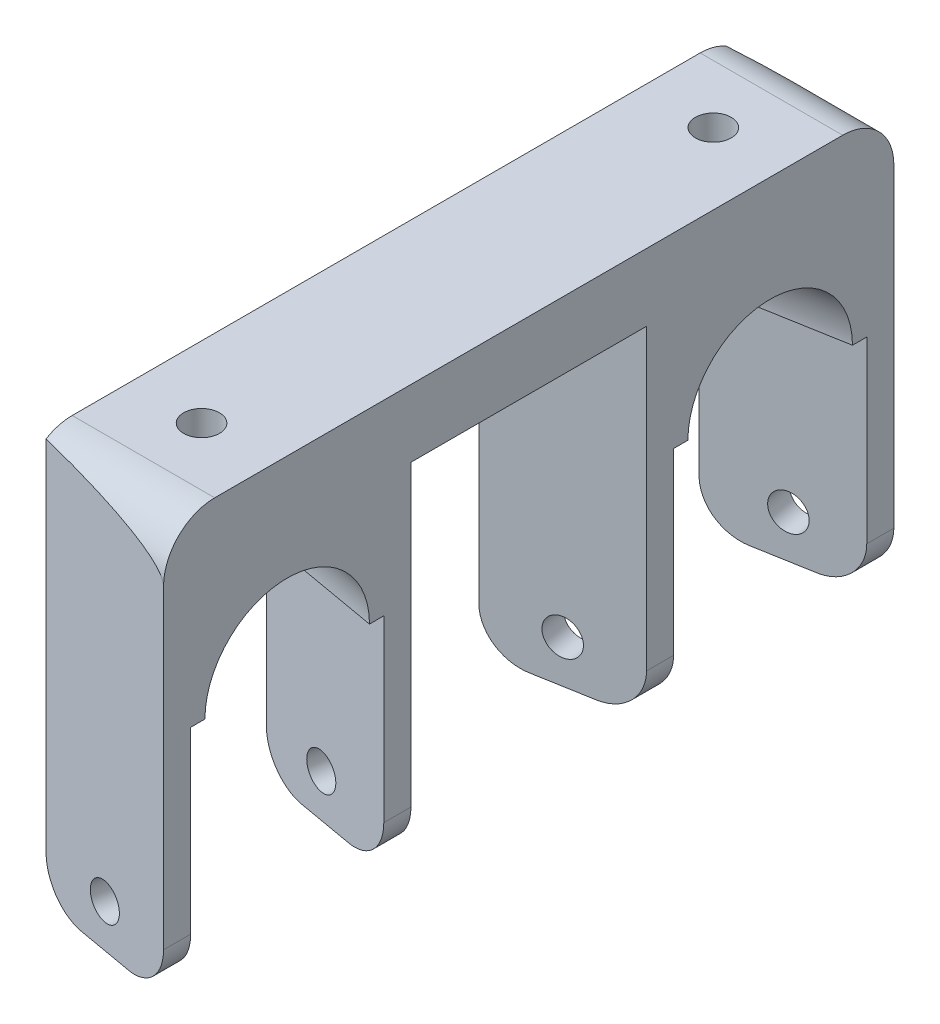
SolidWorks part; units mm, degrees
ref_plane "前视基准面" through (0, 0, 0) normal (0, 0, 1) x (1, 0, 0)
ref_plane "上视基准面" through (0, 0, 0) normal (0, 1, 0) x (1, 0, 0)
ref_plane "右视基准面" through (0, 0, 0) normal (1, 0, 0) x (0, 0, -1)
sketch "Sketch1" plane through (0, 0, 0) normal (0, 0, 1) x (1, 0, 0)
  line L0 (-49.7904, -17.4126) -> (50.2096, -17.4126)
  line L1 (50.2096, -17.4126) -> (50.2096, -9.5139)
  line L2 (50.2096, -9.5139) -> (43.3729, -9.5139) construction
  line L3 (22.3729, 11.7021) -> (43.3729, 11.7021) construction
  line L4 (-49.7904, -1.2703) -> (-49.7904, -17.4126)
  circle A0 centre (22.3729, 11.7021) radius 21
  arc A1 (50.2096, -9.5139) -> (-10.864, 22.6705) centre (22.3729, 11.7021) ccw
  spline S0 degree 2 poles (-49.7904, -1.2703) (-17.5579, 2.3865) (-10.864, 22.6705) knots 0 0 0 1 1 1
  dimension "D3" = 42
  dimension "D1" = 100
extrude "Boss-Extrude1" add sketch "Sketch1" along normal blind 70
sketch "Sketch2" plane through (0, -17.4126, 0) normal (0, -1, 0) x (1, 0, 0)
  line L0 (3.5012, 70) -> (3.5012, 0)
  line L4 (-49.7904, 70) -> (50.2096, 70) construction
  line L5 (3.5012, 60) -> (63.5012, 60)
  line L8 (3.5012, 10) -> (3.5012, 60)
  line L10 (63.5012, 60) -> (63.5012, 10)
  line L11 (63.5012, 10) -> (3.5012, 10)
  line L12 (-49.7904, 0) -> (50.2096, 0) construction
extrude "Cut-Extrude6" cut sketch "Sketch2" against normal blind 1000
sketch "Sketch4" plane through (0, 0, 60) normal (0, 0, -1) x (-1, 0, 0)
  line L0 (-3.5012, -17.4126) -> (-33.5012, -17.4126)
  line L1 (-3.5012, -17.4126) -> (-50.2096, -17.4126) construction
  line L2 (-33.5012, -17.4126) -> (-33.5012, -6.107)
  line L3 (-33.5012, -6.107) -> (-3.5012, 2.4902)
  line L4 (-3.5012, 2.4902) -> (-3.5012, -17.4126)
  arc A0 (-3.5012, 20.9139) -> (-3.5012, 2.4902) centre (-22.3729, 11.7021) ccw construction
  dimension "D1" = 30
extrude "Cut-Extrude7" cut sketch "Sketch4" against normal mid plane 1000
ref_plane "Plane1" through (50.2096, -9.5139, 0) normal (0, 1, 0) x (1, 0, 0)
sketch "Sketch6" plane through (0, -17.4126, 0) normal (0, -1, 0) x (1, 0, 0)
  line L0 (3.5012, 10) -> (-24.7923, 11.9649)
  line L1 (-41.5452, 29.9216) -> (-41.5452, 40.0784)
  line L2 (3.5012, 10) -> (3.5012, 60)
  line L3 (2.8084, 0.024) -> (-25.4851, 1.9889)
  line L4 (-51.5452, 29.9216) -> (-51.5452, 40.0784)
  line L5 (-41.9015, 35) -> (-41.5452, 35) construction
  line L6 (3.5012, 60) -> (-24.7923, 58.0351)
  line L7 (2.8084, 69.976) -> (-25.4851, 68.0111)
  line L8 (2.8084, 0.024) -> (-51.5452, 0.024)
  line L9 (-51.5452, 0.024) -> (-51.5452, 69.976)
  line L10 (-51.5452, 69.976) -> (2.8084, 69.976)
  arc A0 (-24.7923, 11.9649) -> (-41.5452, 29.9216) centre (-23.5452, 29.9216) cw
  arc A1 (-24.7923, 58.0351) -> (-41.5452, 40.0784) centre (-23.5452, 40.0784) ccw
  arc A2 (-25.4851, 1.9889) -> (-51.5452, 29.9216) centre (-23.5452, 29.9216) cw
  arc A3 (-25.4851, 68.0111) -> (-51.5452, 40.0784) centre (-23.5452, 40.0784) ccw
  line M8 (3.5012, 0) -> (3.5012, 70)
  dimension "D1" = 18
  dimension "D3" = 10
extrude "Cut-Extrude9" cut sketch "Sketch6" against normal blind 10 contours L6 A1 L1 A0 L0 M8
sketch "Sketch7" plane through (0, -17.4126, 0) normal (0, -1, 0) x (1, 0, 0)
  line L0 (-23.1446, 0) -> (-26.7904, 0)
  line L1 (-49.7904, 0) -> (3.5012, 0) construction
  line L2 (-49.7904, 70) -> (-49.7904, 0) construction
  line L3 (-26.7904, 0) -> (-51.7904, 0)
  line L4 (-26.7904, 70) -> (-23.1446, 70)
  line L5 (-49.7904, 70) -> (3.5012, 70) construction
  line L6 (-51.7904, 25) -> (-51.7904, 45)
  line L7 (-51.7904, 0) -> (-51.7904, 70)
  line L8 (-51.7904, 70) -> (-26.7904, 70)
  arc A0 (-51.7904, 45) -> (-26.7904, 70) centre (-26.7904, 45) cw
  arc A1 (-26.7904, 0) -> (-51.7904, 25) centre (-26.7904, 25) cw
  point P17 (-51.7904, 0)
  line M5 (3.5012, 70) -> (-49.7904, 70)
  line M6 (-49.7904, 70) -> (-49.7904, 0)
  line M7 (-49.7904, 0) -> (3.5012, 0)
  dimension "D2" = 25
  dimension "D1" = 2
extrude "Cut-Extrude10" cut sketch "Sketch7" against normal blind 30 contours A1 M7 M6 | A1 L7 L3 M6 | L7 A0 L8 M6 | A0 M6 M5 | A1 A0 L6 M6
sketch "Sketch8" plane through (0, 0, 0) normal (0, 1, 0) x (1, 0, 0)
  line L0 (3.5012, -10) -> (3.5012, -60)
  point P4 (3.5012, -35)
ref_plane "Plane3" through (0, 0, 35) normal (0, 0, -1) x (-1, 0, 0)
fillet "Fillet1" radius 10 1 edges at (-49.7904, -1.2703, 35)
sketch "Sketch13" plane through (0, 0, 35) normal (0, 0, -1) x (-1, 0, 0)
  line L0 (-3.5012, 2.4902) -> (-3.5012, 64.347) construction
  line L1 (-3.5012, 41.1785) -> (-24.8842, 72.5913)
  line L2 (-24.8842, 72.5913) -> (-12.5264, 81.0034)
  line L3 (-12.5264, 81.0034) -> (8.0383, 50.7928)
  line L4 (11.0572, 45.7425) -> (33.7918, 2.0647)
  arc A0 (-3.5012, 41.1785) -> (10.864, 22.6705) centre (-22.3729, 11.7021) cw
  arc A1 (10.864, 22.6705) -> (-50.2096, -9.5139) centre (-22.3729, 11.7021) ccw construction
  arc A2 (8.0383, 50.7928) -> (11.0572, 45.7425) centre (-33.2944, 22.6572) cw
  parabola Q0 (26.7904, 4.95) -> (41.7718, -0.0245) focus (25.8084, 23.5741) apex (14.0807, 15.9386) construction
  spline S0 degree 2 poles (10.864, 22.6705) (15.6943, 8.0336) (33.7918, 2.0647) knots 0 0 0 1 1 1
  dimension "D3" = 50
  dimension "D1" = 38
  dimension "D2" = 14.9492
extrude "Boss-Extrude4" add sketch "Sketch13" along normal mid plane 50
fillet "Fillet3" radius 10 2 edges at (18.7053, 76.7973, 10) (18.7053, 76.7973, 60)
sketch "Sketch14" plane through (-29.1201, 19.8224, 0) normal (-0.8267, 0.5627, 0) x (0, 0, 1)
  line L0 (10, 55.7643) -> (60, 55.7643) construction
  line L1 (10, 37.4648) -> (10, 64.0105) construction
  line L2 (60, 37.4648) -> (60, 64.0105) construction
  circle A0 centre (35, 55.7643) radius 4
extrude "Cut-Extrude11" cut sketch "Sketch14" against normal through all
sketch "Sketch16" plane through (0, 0, 70) normal (0, 0, 1) x (1, 0, 0)
  line L0 (3.5012, 2.4902) -> (3.5012, -17.4126) construction
  line L1 (33.5012, -17.4126) -> (33.5012, -6.107) construction
  line L2 (3.5012, -0.5498) -> (3.5012, 2.4902)
  line L3 (33.5012, -7.8533) -> (33.5012, -6.107)
  arc A0 (3.5012, -0.5498) -> (33.5012, -7.8533) centre (22.3729, 11.7021) cw
  arc A1 (3.5012, 2.4902) -> (33.5012, -6.107) centre (22.3729, 11.7021) cw
  line M4 (3.5012, -17.4126) -> (3.5012, 2.4902)
  arc M5 (3.5012, 2.4902) -> (33.5012, -6.107) centre (22.3729, 11.7021) cw
  line M6 (33.5012, -6.107) -> (33.5012, -17.4126)
extrude "Cut-Extrude12" cut sketch "Sketch16" against normal blind 2 contours A0 M4 M5 M6
sketch "Sketch17" plane through (0, 0, 0) normal (0, 0, -1) x (-1, 0, 0)
  line L0 (-3.5012, 2.4902) -> (-3.5012, -17.4126) construction
  line L1 (-33.5012, -17.4126) -> (-33.5012, -6.107) construction
  line L2 (-33.5012, -7.8533) -> (-33.5012, -6.107)
  line L3 (-3.5012, -0.5498) -> (-3.5012, 2.4902)
  arc A0 (-3.5012, -0.5498) -> (-33.5012, -7.8533) centre (-22.3729, 11.7021) ccw
  arc A1 (-3.5012, 2.4902) -> (-33.5012, -6.107) centre (-22.3729, 11.7021) ccw
  arc A2 (-3.5012, 2.4902) -> (-33.5012, -6.107) centre (-22.3729, 11.7021) ccw construction
  line M7 (-33.5012, -17.4126) -> (-33.5012, -6.107)
  arc M8 (-33.5012, -6.107) -> (-3.5012, 2.4902) centre (-22.3729, 11.7021) cw
  line M9 (-3.5012, 2.4902) -> (-3.5012, -17.4126)
extrude "Cut-Extrude13" cut sketch "Sketch17" against normal blind 2 contours A0 M9 M7 M8
sketch "Sketch20" plane through (0, 0, 10) normal (0, 0, 1) x (1, 0, 0)
  line L1 (50.2096, -9.5139) -> (33.5012, -9.5139)
  line L2 (50.2096, -9.5139) -> (50.2096, -17.4126)
  line L3 (50.2096, -17.4126) -> (33.5012, -17.4126)
  line L4 (33.5012, -9.5139) -> (33.5012, -17.4126)
extrude "Boss-Extrude5" add sketch "Sketch20" along normal up to next
sketch "Sketch22" plane through (0, -17.4126, 0) normal (0, -1, 0) x (1, 0, 0)
  line L0 (50.2096, 70) -> (50.2096, 0) construction
  line L1 (50.2096, 6.688) -> (41.3511, 8.25) construction
  line L2 (41.3511, 61.75) -> (41.3511, 8.25)
  line L3 (50.2096, 16.188) -> (33.5012, 19.1341)
  line L4 (41.3511, 61.75) -> (50.2096, 63.312) construction
  line L5 (50.2096, 72.812) -> (50.2096, 53.812)
  line L6 (41.3511, 35) -> (50.2096, 35) construction
  line L7 (33.5012, 0.1341) -> (33.5012, 19.1341)
  line L8 (50.2096, -2.812) -> (50.2096, 16.188)
  line L9 (50.2096, -2.812) -> (33.5012, 0.1341)
  line L10 (33.5012, 70) -> (33.5012, 0) construction
  line L11 (50.2096, 72.812) -> (33.5012, 69.8659)
  line L12 (50.2096, 53.812) -> (33.5012, 50.8659)
  line L13 (33.5012, 50.8659) -> (33.5012, 69.8659)
  line L14 (50.2096, -2.812) -> (50.2096, -7.812)
  line L15 (50.2096, -7.812) -> (33.5012, -4.8659)
  line L16 (33.5012, -4.8659) -> (33.5012, 0.1341)
  line L17 (33.5012, 19.1341) -> (33.5012, 24.1341)
  line L18 (33.5012, 24.1341) -> (50.2096, 21.188)
  line L19 (50.2096, 21.188) -> (50.2096, 16.188)
  line L20 (50.2096, 16.188) -> (50.2096, 21.188)
  line L21 (33.5012, 19.1341) -> (33.5012, 24.1341)
  line L22 (50.2096, 72.812) -> (50.2096, 77.812)
  line L23 (50.2096, 77.812) -> (33.5012, 74.8659)
  line L24 (33.5012, 74.8659) -> (33.5012, 69.8659)
  line L25 (50.2096, 48.812) -> (50.2096, 53.812)
  line L26 (33.5012, 50.8659) -> (33.5012, 45.8659)
  line L27 (33.5012, 45.8659) -> (50.2096, 48.812)
  point P4 (41.3511, 35)
  point P7 (50.2096, 35)
  dimension "D1" = 80
  dimension "D2" = 53.5
  dimension "D3" = 80
  dimension "D4" = 9.5
  dimension "D5" = 9.5
  dimension "D6" = 5
  dimension "D7" = 5
sketch "Sketch26" plane through (0, 0, 0) normal (0, 0, -1) x (-1, 0, 0)
  line L0 (-50.2096, -17.4126) -> (-50.2096, -9.5139)
  line L1 (-50.2096, -17.4126) -> (-33.5012, -17.4126)
  line L2 (-50.2096, -9.5139) -> (-33.5012, -9.5139)
  line L3 (-33.5012, -17.4126) -> (-33.5012, -9.5139)
  line L4 (-33.5012, -17.4126) -> (-33.5012, -7.8533) construction
extrude "Boss-Extrude12" add sketch "Sketch26" along normal up to vertex (7.812 mm away) up to point (50.2096, -17.4126, -7.812)
sketch "Sketch27" plane through (0, 0, 70) normal (0, 0, 1) x (1, 0, 0)
  line L0 (50.2096, -17.4126) -> (50.2096, -9.5139)
  line L1 (50.2096, -17.4126) -> (33.5012, -17.4126)
  line L2 (50.2096, -9.5139) -> (33.5012, -9.5139)
  line L3 (33.5012, -17.4126) -> (33.5012, -9.5139)
  line L4 (33.5012, -17.4126) -> (33.5012, -7.8533) construction
extrude "Boss-Extrude13" add sketch "Sketch27" along normal up to vertex (7.812 mm away) up to point (50.2096, -17.4126, 77.812)
fillet "Fillet4" radius 6 1 edges at (41.8554, -9.5139, -7.812)
fillet "Fillet5" radius 6 1 edges at (41.8554, -9.5139, 77.812)
extrude "Boss-Extrude14" add sketch "Sketch22" along normal blind 40
sketch "Sketch31" plane through (0, -57.4126, 0) normal (0, -1, 0) x (1, 0, 0)
  line L0 (50.2096, 21.188) -> (55.1689, 20.3135)
  line L1 (33.5012, 24.1341) -> (50.2096, 21.188) construction
  line L2 (50.2096, -7.812) -> (55.1689, 20.3135)
  line L3 (50.2096, 21.188) -> (50.2096, -7.812)
  dimension "D1" = 90
extrude "Boss-Extrude15" add sketch "Sketch31" against normal up to vertex (40 mm away)
sketch "Sketch32" plane through (0, -17.4126, 0) normal (0, 1, 0) x (1, 0, 0)
  line L0 (50.2096, -6.688) -> (52.6892, -6.2508)
  line L1 (50.2096, 7.812) -> (55.1689, -20.3135) construction
sketch "Sketch33" plane through (50.0315, 0, -8.8219) normal (0.9848, 0, -0.1736) x (-0.1736, 0, -0.9848)
  line L0 (-15.3052, -17.4126) -> (-15.3052, -57.4126) construction
  line L1 (-1.0255, -57.4126) -> (-29.5849, -57.4126) construction
  line L2 (-5.8052, -31.4126) -> (-5.8052, -57.4126)
  line L3 (-5.8052, -57.4126) -> (-24.8052, -57.4126)
  line L4 (-24.8052, -57.4126) -> (-24.8052, -31.4126)
  arc A0 (-5.8052, -31.4126) -> (-24.8052, -31.4126) centre (-15.3052, -31.4126) ccw
  dimension "D1" = 14
extrude "Cut-Extrude14" cut sketch "Sketch33" against normal through all
sketch "Sketch34" plane through (0, -57.4126, 0) normal (0, -1, 0) x (1, 0, 0)
  line L0 (50.2096, 48.812) -> (55.1689, 49.6865)
  line L1 (55.1689, 49.6865) -> (50.2096, 77.812)
  line L2 (33.5012, 45.8659) -> (50.2096, 48.812) construction
  line L3 (50.2096, 48.812) -> (50.2096, 77.812)
extrude "Boss-Extrude16" add sketch "Sketch34" against normal up to vertex (40 mm away)
sketch "Sketch35" plane through (0, -17.4126, 0) normal (0, 1, 0) x (1, 0, 0)
  line L0 (50.2096, -63.312) -> (52.6892, -63.7492)
  line L1 (55.1689, -49.6865) -> (50.2096, -77.812) construction
  line L2 (41.3511, -61.75) -> (50.2096, -63.312) construction
sketch "Sketch36" plane through (62.0022, 0, 10.9327) normal (0.9848, 0, 0.1736) x (0.1736, 0, -0.9848)
  line L0 (-53.6313, -17.4126) -> (-53.6313, -57.4126) construction
  line L1 (-39.3516, -57.4126) -> (-67.9111, -57.4126) construction
  line L2 (-44.1313, -31.4126) -> (-44.1313, -57.4126)
  line L3 (-44.1313, -57.4126) -> (-63.1313, -57.4126)
  line L4 (-63.1313, -57.4126) -> (-63.1313, -31.4126)
  arc A0 (-44.1313, -31.4126) -> (-63.1313, -31.4126) centre (-53.6313, -31.4126) ccw
  dimension "D1" = 14
extrude "Cut-Extrude16" cut sketch "Sketch36" against normal through all
sketch "Sketch37" plane through (0, -17.4126, 0) normal (0, -1, 0) x (1, 0, 0)
  line L0 (33.5012, -4.8659) -> (33.5012, -7.812)
  line L1 (33.5012, -4.8659) -> (33.5012, -7.812) construction
  line L2 (33.5012, -7.812) -> (50.2096, -7.812)
  line L3 (50.2096, -7.812) -> (33.5012, -4.8659)
extrude "Cut-Extrude17" cut sketch "Sketch37" against normal blind 20
sketch "Sketch38" plane through (0, -17.4126, 0) normal (0, -1, 0) x (1, 0, 0)
  line L0 (50.2096, 77.812) -> (33.5012, 77.812)
  line L1 (33.5012, 77.812) -> (33.5012, 74.8659)
  line L2 (33.5012, 74.8659) -> (50.2096, 77.812)
extrude "Cut-Extrude18" cut sketch "Sketch38" against normal blind 20
sketch "Sketch39" plane through (0, -17.4126, 0) normal (0, 1, 0) x (1, 0, 0)
  line L0 (50.2096, -48.812) -> (55.1689, -49.6865)
  line L1 (55.1689, -49.6865) -> (50.2096, -77.812)
  line L2 (50.2096, -77.812) -> (50.2096, -48.812)
  line L3 (50.2096, 7.812) -> (55.1689, -20.3135)
  line L4 (55.1689, -20.3135) -> (50.2096, -21.188)
  line L5 (50.2096, -21.188) -> (50.2096, 7.812)
extrude "Cut-Extrude19" cut sketch "Sketch39" against normal through all
sketch "Sketch40" plane through (0, 0, 0) normal (0, 0, 1) x (1, 0, 0)
  line L2 (-102.1354, 107.4886) -> (83.1057, 107.4886)
  line L3 (-102.1354, 107.4886) -> (-102.1354, -9.5139)
  line L4 (-102.1354, -9.5139) -> (83.1057, -9.5139)
  line L5 (83.1057, 107.4886) -> (83.1057, -9.5139)
  line L6 (50.2096, -9.5139) -> (33.5012, -9.5139) construction
extrude "Cut-Extrude21" cut sketch "Sketch40" along normal through all
sketch "Sketch41" plane through (0, 0, 0) normal (0, 0, 1) x (1, 0, 0)
  line L1 (-52.6628, 2.4104) -> (15.0327, 2.4104)
  line L2 (-52.6628, 2.4104) -> (-52.6628, -30.0683)
  line L3 (-52.6628, -30.0683) -> (15.0327, -30.0683)
  line L4 (15.0327, 2.4104) -> (15.0327, -30.0683)
extrude "Cut-Extrude22" cut sketch "Sketch41" along normal through all
sketch "Sketch42" plane through (0, -9.5139, 0) normal (0, 1, 0) x (1, 0, 0)
  line L0 (35.2644, 1.812) -> (35.2644, -71.812) construction
  line L1 (50.2096, 1.812) -> (33.5012, 1.812) construction
  line L2 (33.5012, -71.812) -> (50.2096, -71.812) construction
  line L3 (35.2644, -71.812) -> (35.2644, -35) construction
  line L4 (35.2644, -35) -> (88.62, -35) construction
  line L5 (41.8554, -5) -> (41.8554, -65) construction
  line L6 (33.5012, -39.9171) -> (50.2096, -39.9171) construction
  line L7 (33.5012, -71.812) -> (33.5012, 1.812) construction
  line L8 (50.2096, -71.812) -> (50.2096, 1.812) construction
  circle A2 centre (41.8554, -5) radius 2.5
  circle A3 centre (41.8554, -65) radius 2.5
  point P12 (41.8554, -35)
  point P19 (41.8554, -39.9171)
  dimension "D1" = 60
fillet "Fillet6" radius 5 6 edges at (50.2096, -57.4126, -5.3853) (33.5012, -57.4126, -2.4391) (50.2096, -57.4126, 75.3853) (50.2096, -57.4126, 51.2387) (33.5012, -57.4126, 48.2926) (33.5012, -57.4126, 72.4391)
sketch "Sketch75" plane through (-11.7926, 0, 66.8793) normal (-0.1736, 0, 0.9848) x (0.9848, 0, 0.1736)
  line L0 (54.4756, -57.4126) -> (54.4756, -49.4126) construction
  line L1 (57.8815, -57.4126) -> (51.0697, -57.4126) construction
  dimension "D1" = 8
sketch "草图1" plane through (0.1781, 0, 1.0099) normal (-0.1736, 0, -0.9848) x (-0.9848, 0, 0.1736)
  line L0 (-42.3202, -57.4126) -> (-42.3202, -37.8513) construction
  line L1 (-45.7262, -57.4126) -> (-38.9143, -57.4126) construction
  circle A0 centre (-42.3202, -52.4126) radius 1
  dimension "D1" = 5
sketch "Sketch78" plane through (0, -57.4126, 0) normal (0, -1, 0) x (1, 0, 0)
  circle A0 centre (41.8554, 5) radius 4.1
  circle A1 centre (41.8554, 65) radius 4.1
extrude "Cut-Extrude23" cut sketch "Sketch78" against normal blind 40.5
sketch "Sketch80" plane through (0, -16.9126, 0) normal (0, -1, 0) x (1, 0, 0)
  circle A0 centre (41.8554, 65) radius 2.5
  circle A1 centre (41.8554, 5) radius 2.5
hole_wizard "M5 Tapped Hole2" positions "3DSketch4" profile "Sketch82" tap size "M5" standard "GB"
sketch3d "3DSketch4"
  point P0 (41.8554, -16.9126, 65)
  point P3 (41.8554, -16.9126, 5)
sketch "Sketch82" plane through (41.8554, -16.9126, 65) normal (1, 0, 0) x (0, 0, -1)
  line L0 (0, 0) -> (0, 8.6595)
  line L1 (0, 8.6595) -> (2.1, 7.3977)
  line L2 (2.1, 7.3977) -> (2.1, 0)
  line L5 (2.1, 0) -> (0, 0)
  line L10 (0, 8.6595) -> (-2.1, 7.3977) construction
  line L11 (0, -6.35) -> (0, 107.95) construction
  dimension "Tap Drill Dia." = 4.2
  dimension "Tap Drill Depth" = 7.3977
  dimension "Drill Angle" = 118
cosmetic thread "Hole Thread2" parameters "D1"=7.3987, "D2"=5
cosmetic thread "Hole Thread3" parameters "D1"=7.3987, "D2"=5
hole_wizard "M5 Tapped Hole3" positions "3D草图1" profile "草图2" tap size "M5" standard "GB"
sketch3d "3D草图1"
  point P0 (41.8554, -52.4126, -6.3389)
sketch "草图2" plane through (41.8554, -52.4126, -6.3389) normal (0, 1, 0) x (-0.9848, 0, 0.1736)
  line L0 (0, 0) -> (0, 5.2)
  line L1 (0, 5.2) -> (2.1, 3.9382)
  line L2 (2.1, 3.9382) -> (2.1, 0)
  line L5 (2.1, 0) -> (0, 0)
  line L10 (0, 5.2) -> (-2.1, 3.9382) construction
  line L11 (0, -6.35) -> (0, 107.95) construction
  dimension "螺纹孔钻头直径" = 4.2
  dimension "螺纹孔钻头深度" = 5.2
  dimension "导头角度" = 118
cosmetic thread "孔螺蚊线1" parameters "D1"=3.1292, "D2"=5
sketch "草图3" plane through (-11.7926, 0, 66.8793) normal (-0.1736, 0, 0.9848) x (0.9848, 0, 0.1736)
  line L0 (54.4756, -57.4126) -> (54.4756, -49.4126) construction
  circle A0 centre (54.4756, -52.4126) radius 1
  dimension "D1" = 5
hole_wizard "M5 Tapped Hole4" positions "3D草图2" profile "草图4" tap size "M5" standard "GB"
sketch3d "3D草图2"
  point P0 (41.8554, -52.4126, 76.3389)
sketch "草图4" plane through (41.8554, -52.4126, 76.3389) normal (0, 1, 0) x (0.9848, 0, 0.1736)
  line L0 (0, 0) -> (0, 5.2)
  line L1 (0, 5.2) -> (2.1, 3.9382)
  line L2 (2.1, 3.9382) -> (2.1, 0)
  line L5 (2.1, 0) -> (0, 0)
  line L10 (0, 5.2) -> (-2.1, 3.9382) construction
  line L11 (0, -6.35) -> (0, 107.95) construction
  dimension "螺纹孔钻头直径" = 4.2
  dimension "螺纹孔钻头深度" = 5.2
  dimension "导头角度" = 118
cosmetic thread "孔螺蚊线2" parameters "D1"=3.1292, "D2"=5
sketch "草图5" plane through (5.1374, 0, 29.1355) normal (0.1736, 0, 0.9848) x (0.9848, 0, -0.1736)
  line L0 (37.2844, -57.4126) -> (37.2844, -45.6182) construction
  line L1 (33.8785, -57.4126) -> (40.6904, -57.4126) construction
  circle A0 centre (37.2844, -52.4126) radius 1
  dimension "D1" = 5
hole_wizard "M5 Tapped Hole5" positions "3D草图3" profile "草图6" tap size "M5" standard "GB"
sketch3d "3D草图3"
  point P0 (41.8554, -52.4126, 22.6611)
sketch "草图6" plane through (41.8554, -52.4126, 22.6611) normal (0, 1, 0) x (0.9848, 0, -0.1736)
  line L0 (0, 0) -> (0, 5.2)
  line L1 (0, 5.2) -> (2.1, 3.9382)
  line L2 (2.1, 3.9382) -> (2.1, 0)
  line L5 (2.1, 0) -> (0, 0)
  line L10 (0, 5.2) -> (-2.1, 3.9382) construction
  line L11 (0, -6.35) -> (0, 107.95) construction
  dimension "螺纹孔钻头直径" = 4.2
  dimension "螺纹孔钻头深度" = 5.2
  dimension "导头角度" = 118
cosmetic thread "孔螺蚊线3" parameters "D1"=3.1292, "D2"=5
sketch "草图7" plane through (-6.8333, 0, 38.7538) normal (0.1736, 0, -0.9848) x (-0.9848, 0, -0.1736)
  line L0 (-49.4398, -57.4126) -> (-49.4398, -46.1999) construction
  line L1 (-46.0339, -57.4126) -> (-52.8458, -57.4126) construction
  circle A0 centre (-49.4398, -52.4126) radius 1
  dimension "D1" = 5
hole_wizard "M5 Tapped Hole6" positions "3D草图4" profile "草图8" tap size "M5" standard "GB"
sketch3d "3D草图4"
  point P0 (41.8554, -52.4126, 47.3389)
sketch "草图8" plane through (41.8554, -52.4126, 47.3389) normal (0, 1, 0) x (-0.9848, 0, -0.1736)
  line L0 (0, 0) -> (0, 12.4)
  line L1 (0, 12.4) -> (2.1, 11.1382)
  line L2 (2.1, 11.1382) -> (2.1, 0)
  line L5 (2.1, 0) -> (0, 0)
  line L10 (0, 12.4) -> (-2.1, 11.1382) construction
  line L11 (0, -6.35) -> (0, 107.95) construction
  dimension "螺纹孔钻头直径" = 4.2
  dimension "螺纹孔钻头深度" = 12.4
  dimension "导头角度" = 118
cosmetic thread "孔螺蚊线4" parameters "D1"=3.1292, "D2"=5
sketch "Sketch88" plane through (0, -57.4126, 0) normal (0, -1, 0) x (1, 0, 0)
  line L0 (33.5012, -1.6884) -> (50.2096, -4.6345)
  line L1 (33.5012, -4.8659) -> (33.5012, -0.0124) construction
  line L2 (50.2096, -2.9585) -> (50.2096, -7.812) construction
  line L3 (50.2096, -4.6345) -> (50.2096, 18.0105)
  line L4 (50.2096, 18.0105) -> (33.5012, 20.9566)
  line L5 (33.5012, 19.2807) -> (33.5012, 24.1341) construction
  line L6 (33.5012, 20.9566) -> (33.5012, -1.6884)
  line L7 (33.5012, -0.0124) -> (50.2096, -2.9585) construction
  line L8 (50.2096, -2.9585) -> (50.2096, 16.3346) construction
  line L9 (50.2096, 16.3346) -> (33.5012, 19.2807) construction
  line L10 (33.5012, 19.2807) -> (50.2096, -2.9585) construction
  line L11 (33.5012, -0.0124) -> (50.2096, 16.3346) construction
  line L12 (33.5012, -1.6884) -> (50.2096, 18.0105) construction
  line L13 (33.5012, 20.9566) -> (50.2096, -4.6345) construction
  point P14 (41.8554, 8.1611)
  point P19 (41.8554, 8.1611)
  dimension "D1" = 22.645
extrude "Cut-Extrude24" cut sketch "Sketch88" against normal up to vertex (26 mm away) contours L6 L0 L3 L4
sketch "Sketch93" plane through (0, -57.4126, 0) normal (0, -1, 0) x (1, 0, 0)
  line L0 (33.5012, 50.7193) -> (50.2096, 72.9585) construction
  line L1 (33.5012, 70.0124) -> (50.2096, 53.6654) construction
  line L2 (33.5012, 49.0434) -> (50.2096, 51.9895)
  line L3 (33.5012, 49.0434) -> (33.5012, 71.6884)
  line L4 (50.2096, 51.9895) -> (50.2096, 74.6345)
  line L5 (33.5012, 71.6884) -> (50.2096, 74.6345)
  line L6 (33.5012, 45.8659) -> (33.5012, 50.7193) construction
  line L7 (50.2096, 53.6654) -> (50.2096, 48.812) construction
  line L8 (50.2096, 77.812) -> (50.2096, 72.9585) construction
  line L9 (33.5012, 45.8659) -> (50.2096, 48.812) construction
  line L10 (33.5012, 49.0434) -> (50.2096, 74.6345) construction
  line L11 (50.2096, 51.9895) -> (33.5012, 71.6884) construction
  point P20 (41.8554, 61.8389)
  point P21 (41.8554, 61.8389)
  dimension "D1" = 22.645
extrude "Cut-Extrude25" cut sketch "Sketch93" against normal blind 26
